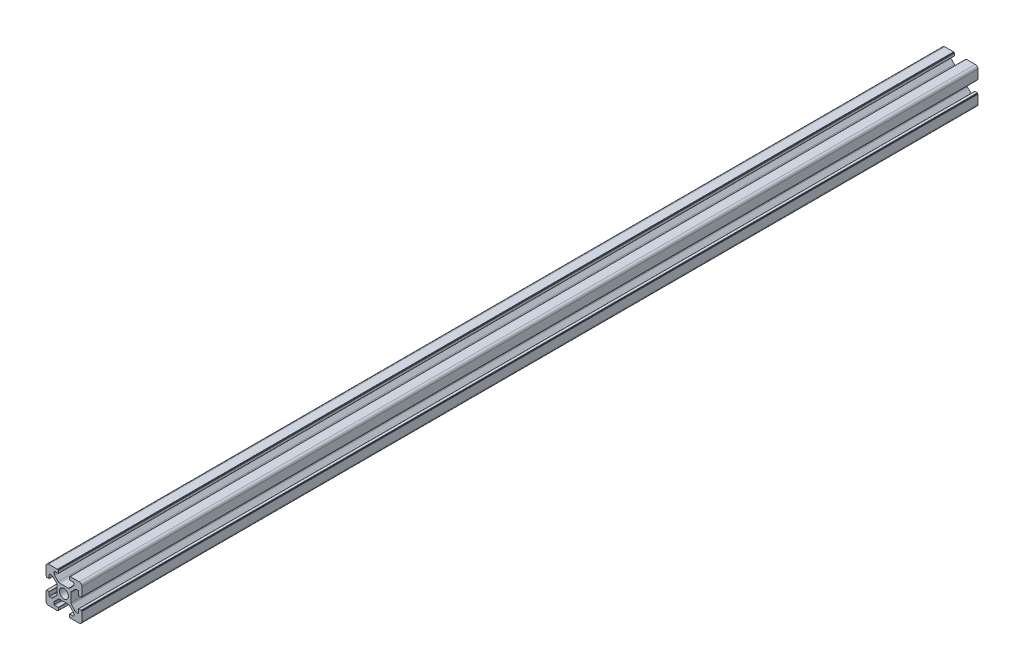
SolidWorks part; units mm, degrees
material "6063-T5"
ref_plane "前视基准面" through (0, 0, 0) normal (0, 0, 1) x (1, 0, 0)
ref_plane "上视基准面" through (0, 0, 0) normal (0, 1, 0) x (1, 0, 0)
ref_plane "右视基准面" through (0, 0, 0) normal (1, 0, 0) x (0, 0, -1)
sketch "草图1" plane through (0, 0, 0) normal (0, 0, 1) x (1, 0, 0)
  line L0 (-1.4389, 10) -> (24.3741, 10) construction
  line L1 (20, 13.6) -> (20, 20)
  line L2 (0, 0) -> (0, 6.4)
  line L3 (0, 20) -> (6.4, 20)
  line L4 (20, 0) -> (20, 6.4)
  line L5 (10, 21.5388) -> (10, -2.4017) construction
  line L6 (6.9, 18.3) -> (6.9, 19.7)
  line L7 (6.8, 18.2) -> (4.8, 18.2)
  line L8 (4.5, 17.9) -> (4.5, 16.9749)
  line L9 (4.7929, 16.2678) -> (6.8678, 14.1929)
  line L10 (7.5749, 13.9) -> (12.4251, 13.9)
  line L11 (6.8, 19.8) -> (6.4, 19.8)
  line L12 (6.4, 19.8) -> (6.4, 20)
  line L13 (0, 13.6) -> (0.2, 13.6)
  line L14 (0.2, 13.6) -> (0.2, 13.2)
  line L15 (0.3, 13.1) -> (1.7, 13.1)
  line L16 (1.8, 13.2) -> (1.8, 15.2)
  line L17 (2.1, 15.5) -> (3.0251, 15.5)
  line L18 (3.7322, 15.2071) -> (5.8071, 13.1322)
  line L19 (6.1, 12.4251) -> (6.1, 7.5749)
  line L20 (13.6, 19.8) -> (13.6, 20)
  line L21 (13.2, 19.8) -> (13.6, 19.8)
  line L22 (13.1, 18.3) -> (13.1, 19.7)
  line L23 (13.2, 18.2) -> (15.2, 18.2)
  line L24 (15.5, 17.9) -> (15.5, 16.9749)
  line L25 (15.2071, 16.2678) -> (13.1322, 14.1929)
  line L26 (0, 6.4) -> (0.2, 6.4)
  line L27 (0.2, 6.4) -> (0.2, 6.8)
  line L28 (0.3, 6.9) -> (1.7, 6.9)
  line L29 (1.8, 6.8) -> (1.8, 4.8)
  line L30 (2.1, 4.5) -> (3.0251, 4.5)
  line L31 (3.7322, 4.7929) -> (5.8071, 6.8678)
  line L32 (13.6, 20) -> (20, 20)
  line L33 (0, 13.6) -> (0, 20)
  line L34 (13.6, 0.2) -> (13.6, 0)
  line L35 (13.2, 0.2) -> (13.6, 0.2)
  line L36 (13.1, 1.7) -> (13.1, 0.3)
  line L37 (13.2, 1.8) -> (15.2, 1.8)
  line L38 (15.5, 2.1) -> (15.5, 3.0251)
  line L39 (15.2071, 3.7322) -> (13.1322, 5.8071)
  line L40 (4.5, 2.1) -> (4.5, 3.0251)
  line L41 (6.8, 1.8) -> (4.8, 1.8)
  line L42 (6.4, 0.2) -> (6.4, 0)
  line L43 (6.8, 0.2) -> (6.4, 0.2)
  line L44 (6.9, 1.7) -> (6.9, 0.3)
  line L45 (4.7929, 3.7322) -> (6.8678, 5.8071)
  line L46 (7.5749, 6.1) -> (12.4251, 6.1)
  line L47 (20, 6.4) -> (19.8, 6.4)
  line L48 (19.8, 6.4) -> (19.8, 6.8)
  line L49 (19.7, 6.9) -> (18.3, 6.9)
  line L50 (18.2, 6.8) -> (18.2, 4.8)
  line L51 (17.9, 4.5) -> (16.9749, 4.5)
  line L52 (16.2678, 4.7929) -> (14.1929, 6.8678)
  line L53 (13.9, 12.4251) -> (13.9, 7.5749)
  line L54 (16.2678, 15.2071) -> (14.1929, 13.1322)
  line L55 (17.9, 15.5) -> (16.9749, 15.5)
  line L56 (18.2, 13.2) -> (18.2, 15.2)
  line L57 (19.7, 13.1) -> (18.3, 13.1)
  line L58 (19.8, 13.6) -> (19.8, 13.2)
  line L59 (20, 13.6) -> (19.8, 13.6)
  line L60 (0, 0) -> (6.4, 0)
  line L61 (13.6, 0) -> (20, 0)
  arc A0 (6.1, 12.4251) -> (5.8071, 13.1322) centre (5.1, 12.4251) ccw
  arc A1 (7.5749, 13.9) -> (6.8678, 14.1929) centre (7.5749, 14.9) cw
  arc A2 (4.5, 16.9749) -> (4.7929, 16.2678) centre (5.5, 16.9749) ccw
  arc A3 (3.7322, 15.2071) -> (3.0251, 15.5) centre (3.0251, 14.5) ccw
  arc A4 (4.5, 17.9) -> (4.8, 18.2) centre (4.8, 17.9) cw
  arc A5 (1.8, 15.2) -> (2.1, 15.5) centre (2.1, 15.2) cw
  arc A6 (0.3, 13.1) -> (0.2, 13.2) centre (0.3, 13.2) cw
  arc A7 (6.9, 19.7) -> (6.8, 19.8) centre (6.8, 19.7) ccw
  arc A8 (1.7, 13.1) -> (1.8, 13.2) centre (1.7, 13.2) ccw
  arc A9 (6.9, 18.3) -> (6.8, 18.2) centre (6.8, 18.3) cw
  arc A10 (13.1, 19.7) -> (13.2, 19.8) centre (13.2, 19.7) cw
  arc A11 (13.1, 18.3) -> (13.2, 18.2) centre (13.2, 18.3) ccw
  arc A12 (15.5, 17.9) -> (15.2, 18.2) centre (15.2, 17.9) ccw
  arc A13 (15.5, 16.9749) -> (15.2071, 16.2678) centre (14.5, 16.9749) cw
  arc A14 (12.4251, 13.9) -> (13.1322, 14.1929) centre (12.4251, 14.9) ccw
  arc A15 (0.3, 6.9) -> (0.2, 6.8) centre (0.3, 6.8) ccw
  arc A16 (1.7, 6.9) -> (1.8, 6.8) centre (1.7, 6.8) cw
  arc A17 (1.8, 4.8) -> (2.1, 4.5) centre (2.1, 4.8) ccw
  arc A18 (3.7322, 4.7929) -> (3.0251, 4.5) centre (3.0251, 5.5) cw
  arc A19 (6.1, 7.5749) -> (5.8071, 6.8678) centre (5.1, 7.5749) cw
  arc A20 (13.1, 0.3) -> (13.2, 0.2) centre (13.2, 0.3) ccw
  arc A21 (13.1, 1.7) -> (13.2, 1.8) centre (13.2, 1.7) cw
  arc A22 (15.5, 2.1) -> (15.2, 1.8) centre (15.2, 2.1) cw
  arc A23 (15.5, 3.0251) -> (15.2071, 3.7322) centre (14.5, 3.0251) ccw
  arc A24 (12.4251, 6.1) -> (13.1322, 5.8071) centre (12.4251, 5.1) cw
  arc A25 (4.5, 2.1) -> (4.8, 1.8) centre (4.8, 2.1) ccw
  arc A26 (6.9, 0.3) -> (6.8, 0.2) centre (6.8, 0.3) cw
  arc A27 (6.9, 1.7) -> (6.8, 1.8) centre (6.8, 1.7) ccw
  arc A28 (4.5, 3.0251) -> (4.7929, 3.7322) centre (5.5, 3.0251) cw
  arc A29 (7.5749, 6.1) -> (6.8678, 5.8071) centre (7.5749, 5.1) ccw
  arc A30 (19.7, 6.9) -> (19.8, 6.8) centre (19.7, 6.8) cw
  arc A31 (18.3, 6.9) -> (18.2, 6.8) centre (18.3, 6.8) ccw
  arc A32 (18.2, 4.8) -> (17.9, 4.5) centre (17.9, 4.8) cw
  arc A33 (16.2678, 4.7929) -> (16.9749, 4.5) centre (16.9749, 5.5) ccw
  arc A34 (13.9, 7.5749) -> (14.1929, 6.8678) centre (14.9, 7.5749) ccw
  arc A35 (13.9, 12.4251) -> (14.1929, 13.1322) centre (14.9, 12.4251) cw
  arc A36 (16.2678, 15.2071) -> (16.9749, 15.5) centre (16.9749, 14.5) cw
  arc A37 (18.2, 15.2) -> (17.9, 15.5) centre (17.9, 15.2) ccw
  arc A38 (18.3, 13.1) -> (18.2, 13.2) centre (18.3, 13.2) cw
  arc A39 (19.7, 13.1) -> (19.8, 13.2) centre (19.7, 13.2) ccw
  circle A40 centre (10, 10) radius 2.5
  point P39 (0.2, 13.1)
  point P42 (6.9, 19.8)
  point P45 (1.8, 13.1)
  point P48 (6.9, 18.2)
  point P66 (10, 13.9)
  point P83 (6.1, 10)
  dimension "D19" = 1
  dimension "D20" = 1
  dimension "D21" = 0.3
  dimension "D22" = 0.1
  dimension "D23" = 5
  dimension "D1" = 20
  dimension "D2" = 20
  dimension "D3" = 10
  dimension "D4" = 10
  dimension "D5" = 1.8
  dimension "D6" = 0.5
  dimension "D7" = 1.6
  dimension "D8" = 3.1
  dimension "D9" = 6.1
  dimension "D10" = 5.5
  dimension "D11" = 3.1
  dimension "D12" = 6.1
  dimension "D13" = 5.5
  dimension "D14" = 1.8
  dimension "D15" = 0.5
  dimension "D16" = 1.5
  dimension "D17" = 45
  dimension "D18" = 1.6
extrude "凸台-拉伸1" add sketch "草图1" along normal blind 500
fillet "圆角1" radius 1.5 4 edges at (20, 0, 250) (0, 0, 250) (0, 20, 250) (20, 20, 250)
